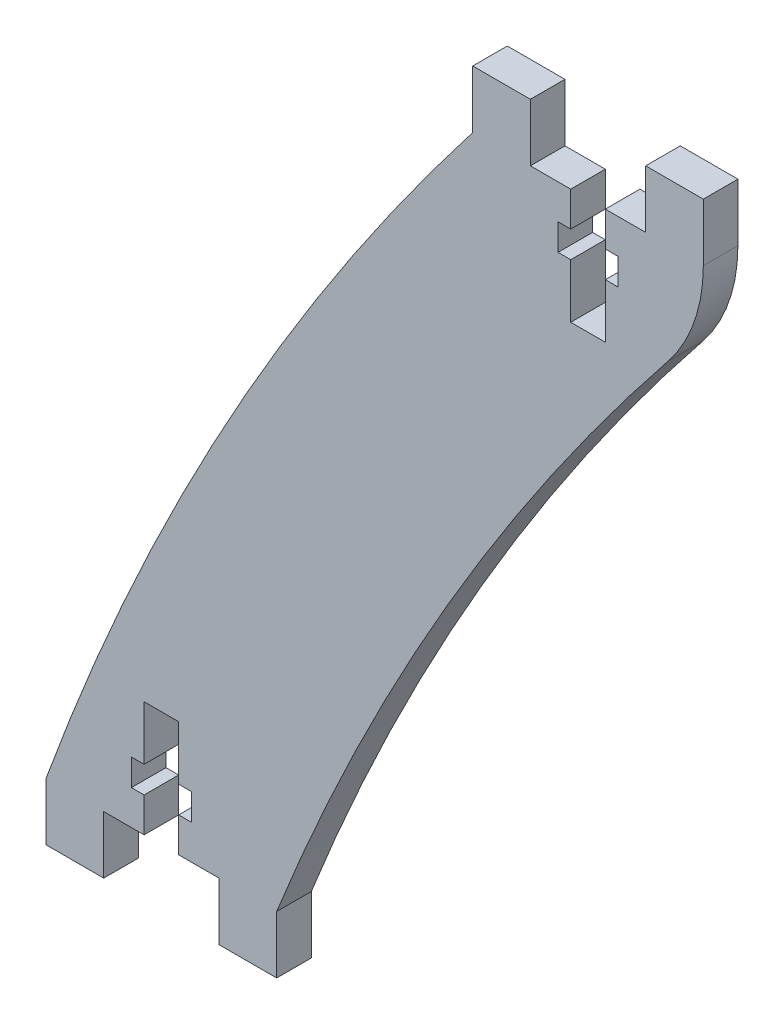
SolidWorks part; units mm, degrees
ref_plane "Front Plane" through (0, 0, 0) normal (0, 0, 1) x (1, 0, 0)
ref_plane "Top Plane" through (0, 0, 0) normal (0, 1, 0) x (1, 0, 0)
ref_plane "Right Plane" through (0, 0, 0) normal (1, 0, 0) x (0, 0, -1)
sketch "Sketch1" plane through (0, 0, 0) normal (0, 0, 1) x (1, 0, 0)
  line L0 (13, 0) -> (13, 67) construction
  line L1 (23, 0) -> (23, 65.2704) construction
  line L2 (13, 67) -> (70, 67) construction
  line L3 (13, 0) -> (22.2995, 25.5503) construction
  line L4 (0, 0) -> (61.5031, 0) construction
  line L5 (70, 67) -> (70, 49.2739) construction
  line L6 (60, 67) -> (60, 55.7792) construction
  line L7 (61.5, 67) -> (65, 67)
  line L8 (65, 72) -> (70, 72)
  line L9 (70, 72) -> (70, 67)
  line L10 (65, 72) -> (65, 67)
  line L11 (58.5, 67) -> (55, 67)
  line L12 (55, 67) -> (55, 72)
  line L13 (55, 72) -> (50, 72)
  line L14 (50, 72) -> (50, 67)
  line L15 (61.5, 67) -> (58.5, 67) construction
  line L16 (58.5, 67) -> (58.5, 64)
  line L17 (58.5, 61.7) -> (57.4, 61.7)
  line L18 (62.6, 64) -> (62.6, 61.7)
  line L19 (57.4, 64) -> (58.5, 64)
  line L20 (58.5, 61.7) -> (58.5, 57)
  line L21 (58.5, 57) -> (61.5, 57)
  line L22 (61.5, 57) -> (61.5, 61.7)
  line L23 (61.5, 64) -> (62.6, 64)
  line L24 (57.4, 61.7) -> (57.4, 64)
  line L25 (62.6, 61.7) -> (61.5, 61.7)
  line L26 (61.5, 64) -> (61.5, 67)
  line L27 (60, 57) -> (60, 67) construction
  line L28 (23, 0) -> (23, 11.2208) construction
  line L29 (21.5, 0) -> (18, 0)
  line L30 (18, -5) -> (13, -5)
  line L31 (13, -5) -> (13, 0)
  line L32 (18, -5) -> (18, 0)
  line L33 (24.5, 0) -> (28, 0)
  line L34 (28, 0) -> (28, -5)
  line L35 (28, -5) -> (33, -5)
  line L36 (33, -5) -> (33, 0)
  line L37 (21.5, 0) -> (24.5, 0) construction
  line L38 (24.5, 0) -> (24.5, 3)
  line L39 (24.5, 5.3) -> (25.6, 5.3)
  line L40 (20.4, 3) -> (20.4, 5.3)
  line L41 (25.6, 3) -> (24.5, 3)
  line L42 (24.5, 5.3) -> (24.5, 10)
  line L43 (24.5, 10) -> (21.5, 10)
  line L44 (21.5, 10) -> (21.5, 5.3)
  line L45 (21.5, 3) -> (20.4, 3)
  line L46 (25.6, 5.3) -> (25.6, 3)
  line L47 (20.4, 5.3) -> (21.5, 5.3)
  line L48 (21.5, 3) -> (21.5, 0)
  line L49 (23, 10) -> (23, 0) construction
  arc A0 (13, 0) -> (50, 67) centre (245.2024, -84.5148) cw
  arc A1 (70, 67) -> (66.9462, 58.3045) centre (56.0931, 67) cw
  arc A2 (66.9462, 58.3045) -> (33, 0) centre (245.2024, -84.5148) ccw
  point P0 (23, 10)
  point P48 (13, 0)
  dimension "D1" = 67
  dimension "D2" = 23
  dimension "D3" = 5.2
  dimension "D4" = 20
  dimension "D5" = 10
  dimension "D6" = 5
  dimension "D7" = 5
  dimension "D8" = 3
  dimension "D9" = 2.3
  dimension "D10" = 3
  dimension "D11" = 10
  dimension "D12" = 10
  dimension "D13" = 5
  dimension "D14" = 5
  dimension "D15" = 5.2
  dimension "D16" = 3
  dimension "D17" = 2.3
  dimension "D18" = 3
  dimension "D19" = 10
  dimension "D20" = 60
extrude "Boss-Extrude1" add sketch "Sketch1" along normal blind 3
